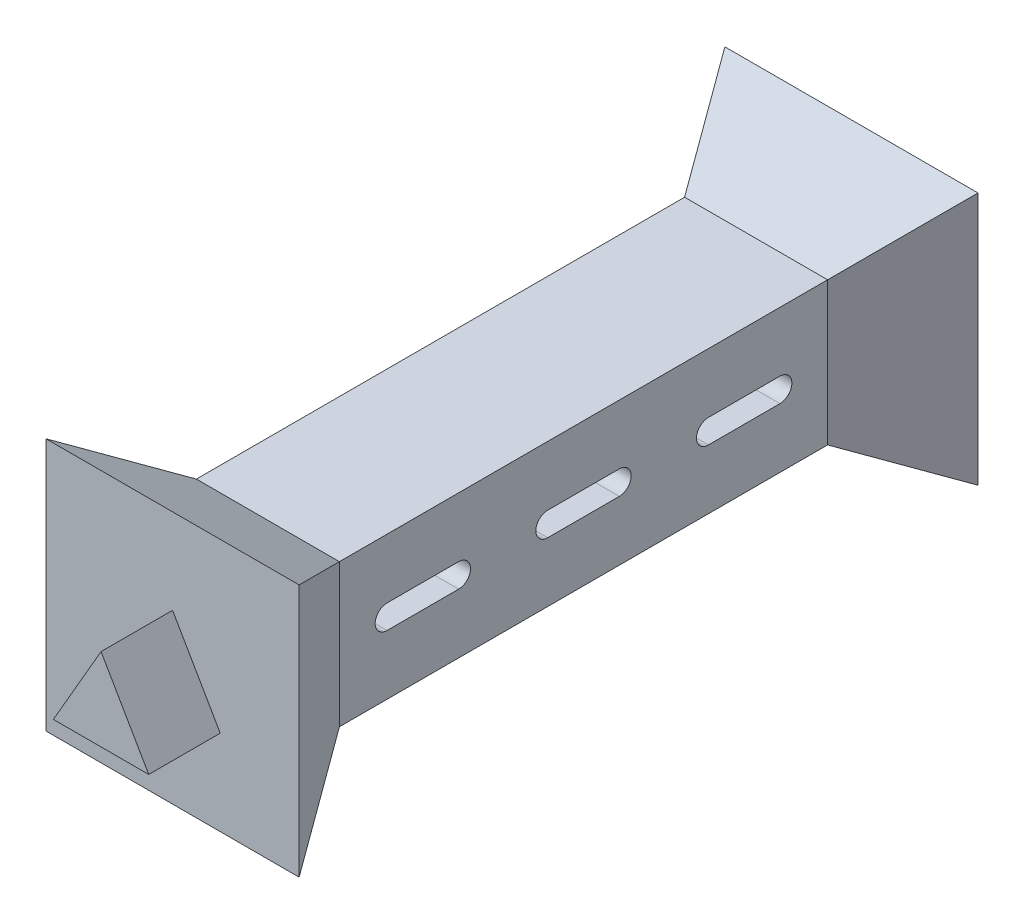
SolidWorks part; units mm, degrees
ref_plane "Front Plane" through (0, 0, 0) normal (0, 0, 1) x (1, 0, 0)
ref_plane "Top Plane" through (0, 0, 0) normal (0, 1, 0) x (1, 0, 0)
ref_plane "Right Plane" through (0, 0, 0) normal (1, 0, 0) x (0, 0, -1)
sketch "Sketch1" plane through (0, 0, 0) normal (0, 0, 1) x (1, 0, 0)
  line L1 (-1.5, 1.5) -> (1.5, 1.5)
  line L2 (-1.5, 1.5) -> (-1.5, -1.5)
  line L3 (-1.5, -1.5) -> (1.5, -1.5)
  line L4 (1.5, 1.5) -> (1.5, -1.5)
  line L5 (-1.5, 1.5) -> (1.5, -1.5) construction
  line L6 (-1.5, -1.5) -> (1.5, 1.5) construction
  point P0 (0, 0)
  dimension "D1" = 3
extrude "Boss-Extrude1" add sketch "Sketch1" along normal blind 10.24
ref_plane "Plane1" through (0, 0, 5.12) normal (0, 0, 1) x (1, 0, 0)
sketch "Sketch2" plane through (0, 0, 10.24) normal (0, 0, 1) x (1, 0, 0)
  line L4 (1.5, -1.5) -> (1.5, 1.5)
  line L5 (1.5, 1.5) -> (-1.5, 1.5)
  line L6 (-1.5, 1.5) -> (-1.5, -1.5)
  line L7 (-1.5, -1.5) -> (1.5, -1.5)
  line L8 (1.5, -1.5) -> (1.5, 1.5)
  line L9 (1.5, 1.5) -> (-1.5, 1.5)
  line L10 (-1.5, 1.5) -> (-1.5, -1.5)
  line L11 (-1.5, -1.5) -> (1.5, -1.5)
  dimension "D1" = 0
extrude "Boss-Extrude2" add sketch "Sketch2" along normal blind 2 draft 30 draft outward yes
mirror "Mirror1" about plane through (0, 0, 5.12) normal (0, 0, 1) of "Boss-Extrude2"
sketch "Sketch3" plane through (0, 0, 12.24) normal (0, 0, 1) x (1, 0, 0)
  line L0 (0, 0.866) -> (-1, -0.866)
  line L1 (-1, -0.866) -> (1, -0.866)
  line L2 (1, -0.866) -> (0, 0.866)
  line L3 (0, 0.866) -> (0, -0.866) construction
  line L4 (-0.5, 0) -> (1, -0.866) construction
  line L5 (-1, -0.866) -> (0.5, 0) construction
  line L6 (0, 2.6547) -> (0, -2.6547) construction
  line L7 (2.6547, 2.6547) -> (-2.6547, 2.6547) construction
  line L8 (-2.6547, -2.6547) -> (2.6547, -2.6547) construction
  line L9 (-2.6547, 0) -> (2.6547, 0) construction
  line L10 (-2.6547, 2.6547) -> (-2.6547, -2.6547) construction
  line L11 (2.6547, -2.6547) -> (2.6547, 2.6547) construction
  point P13 (0, 0)
  dimension "D1" = 2
extrude "Boss-Extrude3" add sketch "Sketch3" along normal blind 1.5
mirror "Mirror2" about plane through (0, 0, 5.12) normal (0, 0, 1) of "Boss-Extrude3"
sketch "Sketch7" plane through (1.5, 0, 0) normal (1, 0, 0) x (0, 0, -1)
  line L0 (-9.24, 0) -> (-7.74, 0) construction
  line L1 (-9.24, 0.25) -> (-7.74, 0.25)
  line L2 (-9.24, -0.25) -> (-7.74, -0.25)
  line L3 (-10.24, -1.5) -> (-10.24, 1.5) construction
  line L4 (-5.87, 0) -> (-4.37, 0) construction
  line L5 (-5.87, 0.25) -> (-4.37, 0.25)
  line L6 (-5.87, -0.25) -> (-4.37, -0.25)
  line L7 (-2.5, 0) -> (-1, 0) construction
  line L8 (-2.5, 0.25) -> (-1, 0.25)
  line L9 (-2.5, -0.25) -> (-1, -0.25)
  line L10 (0, 1.5) -> (0, -1.5) construction
  arc A0 (-9.24, 0.25) -> (-9.24, -0.25) centre (-9.24, 0) ccw
  arc A1 (-7.74, -0.25) -> (-7.74, 0.25) centre (-7.74, 0) ccw
  arc A2 (-5.87, 0.25) -> (-5.87, -0.25) centre (-5.87, 0) ccw
  arc A3 (-4.37, -0.25) -> (-4.37, 0.25) centre (-4.37, 0) ccw
  arc A4 (-2.5, 0.25) -> (-2.5, -0.25) centre (-2.5, 0) ccw
  arc A5 (-1, -0.25) -> (-1, 0.25) centre (-1, 0) ccw
  point P3 (-8.49, 0)
  point P11 (-10.24, 0)
  point P15 (-5.12, 0)
  point P22 (-1.75, 0)
  dimension "D1" = 1.5
  dimension "D3" = 1
  dimension "D5" = 1
  dimension "D2" = 0.5
  dimension "D4" = 3
extrude "Cut-Extrude1" cut sketch "Sketch7" against normal up to next
